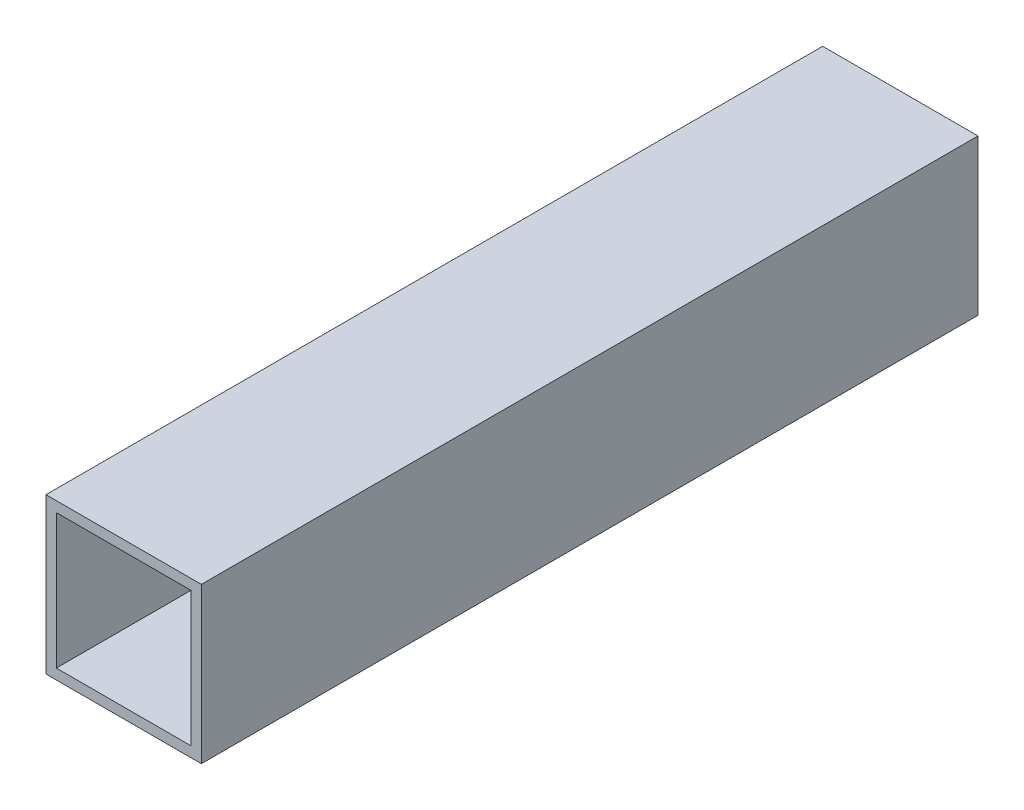
SolidWorks part; units mm, degrees
material "Aleación 1060"
ref_plane "Alzado" through (0, 0, 0) normal (0, 0, 1) x (1, 0, 0)
ref_plane "Planta" through (0, 0, 0) normal (0, 1, 0) x (1, 0, 0)
ref_plane "Vista lateral" through (0, 0, 0) normal (1, 0, 0) x (0, 0, -1)
sketch "Croquis1" plane through (0, 0, 0) normal (0, 0, 1) x (1, 0, 0)
  line L1 (15, -15) -> (-15, -15)
  line L2 (15, -15) -> (15, 15)
  line L3 (15, 15) -> (-15, 15)
  line L4 (-15, -15) -> (-15, 15)
  line L5 (15, -15) -> (-15, 15) construction
  line L6 (15, 15) -> (-15, -15) construction
  point P0 (0, 0)
  dimension "D1" = 30
  dimension "D2" = 30
extrude "Extruir-Lámina1" add sketch "Croquis1" along normal blind 150 thin
